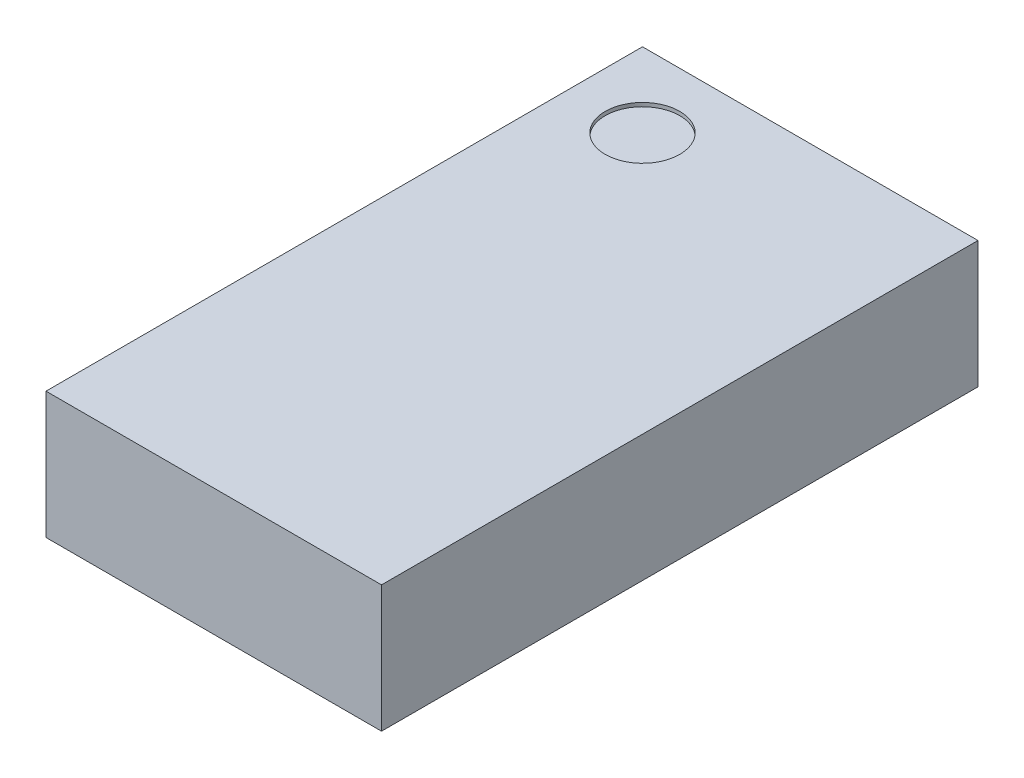
SolidWorks part; units mm, degrees
ref_plane "Front Plane" through (0, 0, 0) normal (0, 0, 1) x (1, 0, 0)
ref_plane "Top Plane" through (0, 0, 0) normal (0, 1, 0) x (1, 0, 0)
ref_plane "Right Plane" through (0, 0, 0) normal (1, 0, 0) x (0, 0, -1)
ref_plane "Plane1" through (0, 0.16, 0) normal (0, 1, 0) x (1, 0, 0)
sketch "Sketch1" plane through (0, 0.16, 0) normal (0, 1, 0) x (1, 0, 0)
  line L1 (-0.45, -0.8) -> (0.45, -0.8)
  line L2 (-0.45, -0.8) -> (-0.45, 0.8)
  line L3 (-0.45, 0.8) -> (0.45, 0.8)
  line L4 (0.45, -0.8) -> (0.45, 0.8)
  line L5 (-0.45, -0.8) -> (0.45, 0.8) construction
  line L6 (-0.45, 0.8) -> (0.45, -0.8) construction
  point P0 (0, 0)
  dimension "D1" = 0.9
  dimension "D2" = 1.6
extrude "Boss-Extrude1" add sketch "Sketch1" along normal offset from surface (0.34 mm away) 0.5 up to plane "Top Plane"
sketch "Sketch3" plane through (0, 0.5, 0) normal (0, 1, 0) x (1, 0, 0)
  line L0 (-0.45, 0.8) -> (-0.45, -0.8) construction
  line L1 (0.45, 0.8) -> (-0.45, 0.8) construction
  circle A0 centre (-0.25, 0.6) radius 0.1
  dimension "D1" = 0.2
  dimension "D3" = 0.2
  dimension "D2" = 0.2
extrude "Cut-Extrude1" cut sketch "Sketch3" against normal blind 0.01
sketch "Sketch2" plane through (0, 0, 0) normal (0, 0, 1) x (1, 0, 0)
  line L0 (0, 0) -> (-0.4619, 0) construction
  line L1 (-0.2, 0.23) -> (-0.2, 0) construction
  line L2 (-0.2, 0.23) -> (-0.2, 0)
  arc A0 (-0.2, 0.23) -> (-0.2, 0) centre (-0.2, 0.115) ccw
  dimension "D1" = 0.23
  dimension "D2" = 0.2
revolve "Revolve3" add sketch "Sketch2" angle 360 about L2
pattern_linear "LPattern1" count 2 spacing 0.4 along (0, 0, -1) count 2 spacing 0.4 along (0, 0, 1) of "Revolve3"
mirror "Mirror1" about plane through (0, 0, 0) normal (1, 0, 0) of "LPattern1", "Revolve3"
